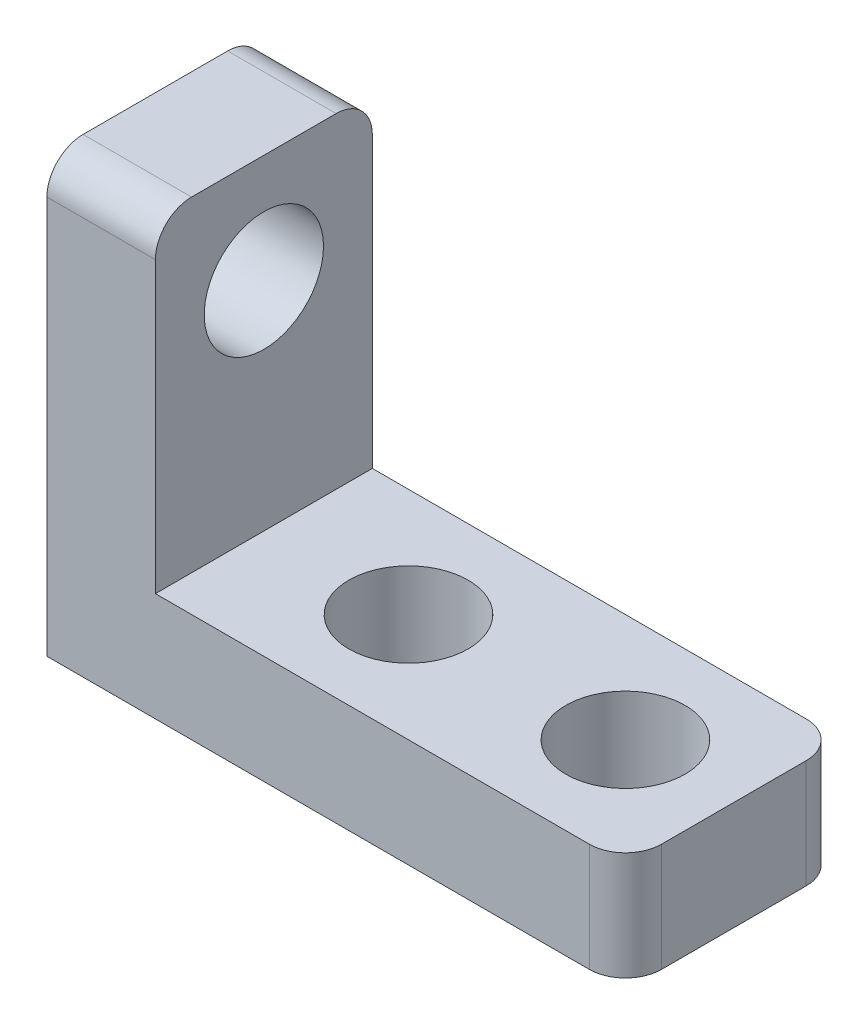
SolidWorks part; units mm, degrees
ref_plane "前视基准面" through (0, 0, 0) normal (0, 0, 1) x (1, 0, 0)
ref_plane "上视基准面" through (0, 0, 0) normal (0, 1, 0) x (1, 0, 0)
ref_plane "右视基准面" through (0, 0, 0) normal (1, 0, 0) x (0, 0, -1)
sketch "草图1" plane through (0, 0, 0) normal (0, 0, 1) x (1, 0, 0)
  line L0 (0, 0) -> (16, 0)
  line L1 (0, 0) -> (0, 12)
  line L2 (0, 12) -> (3, 12)
  line L3 (3, 12) -> (3, 3)
  line L4 (3, 3) -> (16, 3)
  line L5 (16, 3) -> (16, 0)
  dimension "D1" = 16
  dimension "D2" = 12
  dimension "D3" = 3
  dimension "D4" = 9
extrude "凸台-拉伸1" add sketch "草图1" along normal blind 6
sketch "草图2" plane through (3, 0, 0) normal (1, 0, 0) x (0, 0, -1)
  line L0 (-6, 3) -> (-6, 12) construction
  line L1 (-6, 12) -> (0, 12) construction
  circle A0 centre (-3, 9) radius 1.65
  dimension "D1" = 3.3
  dimension "D2" = 3
  dimension "D3" = 3
extrude "切除-拉伸1" cut sketch "草图2" against normal blind 6
sketch "草图3" plane through (0, 3, 0) normal (0, 1, 0) x (1, 0, 0)
  line L0 (3, -6) -> (3, 0) construction
  line L1 (16, -6) -> (3, -6) construction
  circle A0 centre (7, -3) radius 1.65
  circle A1 centre (13, -3) radius 1.65
  dimension "D1" = 3.3
  dimension "D2" = 3.3
  dimension "D3" = 6
  dimension "D4" = 4
  dimension "D5" = 3
extrude "切除-拉伸2" cut sketch "草图3" against normal blind 6
fillet "圆角1" radius 1 4 edges at (1.5, 12, 6) (1.5, 12, 0) (16, 1.5, 0) (16, 1.5, 6)
